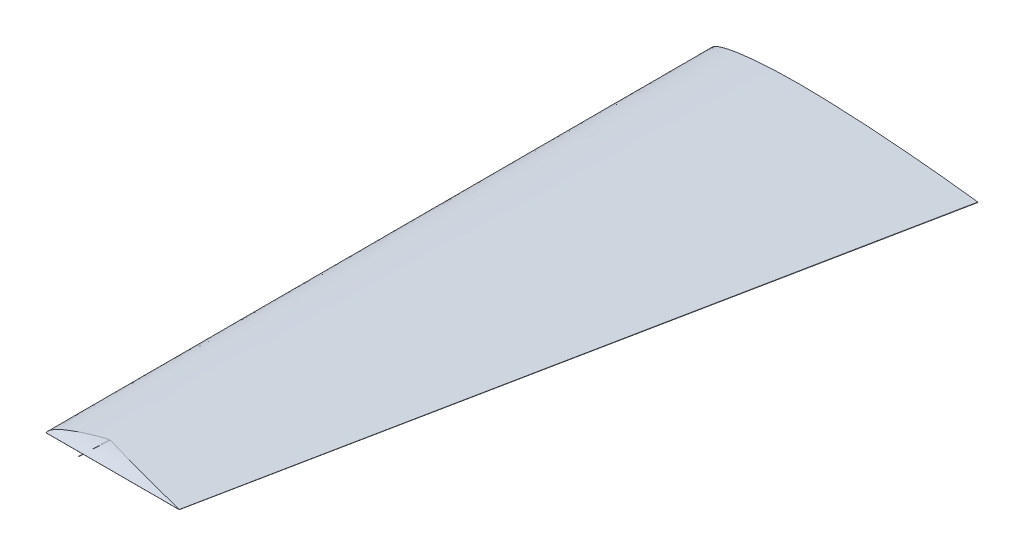
SolidWorks part; units mm, degrees
ref_plane "Front Plane" through (0, 0, 0) normal (0, 0, 1) x (1, 0, 0)
ref_plane "Top Plane" through (0, 0, 0) normal (0, 1, 0) x (1, 0, 0)
ref_plane "Right Plane" through (0, 0, 0) normal (1, 0, 0) x (0, 0, -1)
curve "Curve1"
  spline degree 3 poles (200, 0.17, 0) (196.6775, 0.5867, 0) (190.0326, 1.42, 0) (176.7282, 2.9261, 0) (160.0842, 4.6599, 0) (140.0892, 6.4408, 0) (120.0741, 7.9142, 0) (100.046, 9.0618, 0) (79.9874, 9.8383, 0) (63.2481, 9.9959, 0) (49.8489, 9.6797, 0) (39.8033, 9.2044, 0) (29.7661, 8.4006, 0) (21.4188, 7.4226, 0) (14.7487, 6.3109, 0) (9.7762, 5.2733, 0) (5.5313, 3.9978, 0) (2.2028, 2.7626, 0) (-1.329, -0.0643, 0) (2.4561, -2.5223, 0) (5.8713, -3.4557, 0) (10.1965, -4.3374, 0) (15.2062, -4.9476, 0) (21.8886, -5.5204, 0) (30.2063, -5.9612, 0) (40.1858, -6.1798, 0) (50.1467, -6.2189, 0) (63.418, -6.1197, 0) (80.0231, -5.7775, 0) (99.9664, -5.1377, 0) (119.9393, -4.3294, 0) (139.9252, -3.4016, 0) (159.9318, -2.4016, 0) (176.6142, -1.5068, 0) (189.9743, -0.7666, 0) (196.6568, -0.369, 0) (200, -0.17, 0) knots 0 0 0 0 0.024881 0.04976 0.099487 0.149219 0.198914 0.248605 0.298274 0.348059 0.372958 0.397855 0.422778 0.447754 0.460312 0.472933 0.48573 0.492374 0.501196 0.509997 0.516623 0.529388 0.541926 0.554358 0.579138 0.603839 0.628509 0.653154 0.702452 0.751913 0.801415 0.850979 0.900577 0.950258 0.975115 1 1 1 1
sketch "Sketch1" plane through (0, 0, 0) normal (0, 0, 1) x (1, 0, 0)
  ellipse E0 centre (199.9998, 0.0002) end of major axis (199.8053, 0.0004) minor radius 0.1698 (200.0101, -0.1694) -> (200, 0.17) ccw
  spline S0 degree 3 poles (885.8216, 1859.4461) (495.7124, -79.428) (342.28, -15.8147) (176.7282, 2.9261) (160.0842, 4.6599) (140.0892, 6.4408) (120.0741, 7.9142) (100.046, 9.0618) (79.9874, 9.8383) (63.2481, 9.9959) (49.8489, 9.6797) (39.8033, 9.2044) (29.7661, 8.4006) (21.4188, 7.4226) (14.7487, 6.3109) (9.7762, 5.2733) (5.5313, 3.9978) (2.2028, 2.7626) (-1.329, -0.0643) (2.4561, -2.5223) (5.8713, -3.4557) (10.1965, -4.3374) (15.2062, -4.9476) (21.8886, -5.5204) (30.2063, -5.9612) (40.1858, -6.1798) (50.1467, -6.2189) (63.418, -6.1197) (80.0231, -5.7775) (99.9664, -5.1377) (119.9393, -4.3294) (139.9252, -3.4016) (159.9318, -2.4016) (176.6142, -1.5068) (406.1652, 11.2103) (627.288, 53.9902) (955.0059, -1812.8273) knots -1.138472 -1.138472 -1.138472 -1.138472 0.024881 0.04976 0.099487 0.149219 0.198914 0.248605 0.298274 0.348059 0.372958 0.397855 0.422778 0.447754 0.460312 0.472933 0.48573 0.492374 0.501196 0.509997 0.516623 0.529388 0.541926 0.554358 0.579138 0.603839 0.628509 0.653154 0.702452 0.751913 0.801415 0.850979 0.900577 0.950258 0.975115 2.608853 2.608853 2.608853 2.608853 only from (200, 0.17) to (200, -0.17) construction
  spline S1 degree 3 poles (200, 0.17) (196.6775, 0.5867) (190.0326, 1.42) (176.7282, 2.9261) (160.0842, 4.6599) (140.0892, 6.4408) (120.0741, 7.9142) (100.046, 9.0618) (79.9874, 9.8383) (63.2481, 9.9959) (49.8489, 9.6797) (39.8033, 9.2044) (29.7661, 8.4006) (21.4188, 7.4226) (14.7487, 6.3109) (9.7762, 5.2733) (5.5313, 3.9978) (2.2028, 2.7626) (-1.329, -0.0643) (2.4561, -2.5223) (5.8713, -3.4557) (10.1965, -4.3374) (15.2062, -4.9476) (21.8886, -5.5204) (30.2063, -5.9612) (40.1858, -6.1798) (50.1467, -6.2189) (63.418, -6.1197) (80.0231, -5.7775) (99.9664, -5.1377) (119.9393, -4.3294) (139.9252, -3.4016) (159.9318, -2.4016) (176.6142, -1.5068) (189.9776, -0.7664) (196.6635, -0.3686) (200.0101, -0.1694) knots 0 0 0 0 0.024881 0.04976 0.099487 0.149219 0.198914 0.248605 0.298274 0.348059 0.372958 0.397855 0.422778 0.447754 0.460312 0.472933 0.48573 0.492374 0.501196 0.509997 0.516623 0.529388 0.541926 0.554358 0.579138 0.603839 0.628509 0.653154 0.702452 0.751913 0.801415 0.850979 0.900577 0.950258 0.975115 1.000025 1.000025 1.000025 1.000025
ref_plane "Plane1" through (0, 0, 500) normal (0, 0, 1) x (1, 0, 0)
curve "Curve5"
  spline degree 3 poles (100, 0.08, 0) (98.3405, 0.2906, 0) (95.0201, 0.7118, 0) (88.3671, 1.4611, 0) (80.0448, 2.341, 0) (70.042, 3.2097, 0) (60.0357, 3.9596, 0) (50.0213, 4.5302, 0) (39.9937, 4.9197, 0) (31.6258, 4.9969, 0) (24.9243, 4.8416, 0) (19.902, 4.5944, 0) (14.8795, 4.2015, 0) (10.7092, 3.7129, 0) (7.3761, 3.1547, 0) (4.8922, 2.6348, 0) (2.7648, 2.0026, 0) (1.1046, 1.3748, 0) (-0.665, -0.0316, 0) (1.2285, -1.2612, 0) (2.9335, -1.7282, 0) (5.096, -2.1607, 0) (7.6008, -2.4764, 0) (10.9444, -2.7587, 0) (15.1066, -2.9752, 0) (20.0929, -3.0828, 0) (25.0733, -3.1129, 0) (31.7073, -3.0495, 0) (40.0115, -2.8896, 0) (49.9852, -2.5782, 0) (59.971, -2.156, 0) (69.9643, -1.6971, 0) (79.9641, -1.194, 0) (88.3039, -0.7534, 0) (94.984, -0.3843, 0) (98.3268, -0.1815, 0) (100, -0.08, 0) knots 0 0 0 0 0.02486 0.049739 0.099494 0.149222 0.198943 0.24861 0.298279 0.348065 0.372939 0.397887 0.422784 0.447785 0.460294 0.472915 0.485736 0.49239 0.501194 0.509994 0.51662 0.529357 0.541897 0.554379 0.579134 0.60386 0.62848 0.65315 0.702448 0.751909 0.801438 0.850977 0.900576 0.950232 0.975088 1 1 1 1
sketch "Sketch8" plane through (0, 0, 500) normal (0, 0, 1) x (1, 0, 0)
  ellipse E0 centre (100, 0) end of major axis (100.0982, 0) minor radius 0.08 (100, -0.08) -> (100, 0.08) ccw
  spline S0 degree 3 poles (610.1015, 1926.9997) (277.2849, -58.4947) (186.7781, -9.6222) (88.3671, 1.4611) (80.0448, 2.341) (70.042, 3.2097) (60.0357, 3.9596) (50.0213, 4.5302) (39.9937, 4.9197) (31.6258, 4.9969) (24.9243, 4.8416) (19.902, 4.5944) (14.8795, 4.2015) (10.7092, 3.7129) (7.3761, 3.1547) (4.8922, 2.6348) (2.7648, 2.0026) (1.1046, 1.3748) (-0.665, -0.0316) (1.2285, -1.2612) (2.9335, -1.7282) (5.096, -2.1607) (7.6008, -2.4764) (10.9444, -2.7587) (15.1066, -2.9752) (20.0929, -3.0828) (25.0733, -3.1129) (31.7073, -3.0495) (40.0115, -2.8896) (49.9852, -2.5782) (59.971, -2.156) (69.9643, -1.6971) (79.9641, -1.194) (88.3039, -0.7534) (221.5079, 6.6074) (349.795, 40.9391) (592.8579, -1925.435) knots -1.372215 -1.372215 -1.372215 -1.372215 0.02486 0.049739 0.099494 0.149222 0.198943 0.24861 0.298279 0.348065 0.372939 0.397887 0.422784 0.447785 0.460294 0.472915 0.485736 0.49239 0.501194 0.509994 0.51662 0.529357 0.541897 0.554379 0.579134 0.60386 0.62848 0.65315 0.702448 0.751909 0.801438 0.850977 0.900576 0.950232 0.975088 2.883134 2.883134 2.883134 2.883134 only from (100, 0.08) to (100, -0.08) construction
  spline S1 degree 3 poles (100, 0.08) (98.3405, 0.2906) (95.0201, 0.7118) (88.3671, 1.4611) (80.0448, 2.341) (70.042, 3.2097) (60.0357, 3.9596) (50.0213, 4.5302) (39.9937, 4.9197) (31.6258, 4.9969) (24.9243, 4.8416) (19.902, 4.5944) (14.8795, 4.2015) (10.7092, 3.7129) (7.3761, 3.1547) (4.8922, 2.6348) (2.7648, 2.0026) (1.1046, 1.3748) (-0.665, -0.0316) (1.2285, -1.2612) (2.9335, -1.7282) (5.096, -2.1607) (7.6008, -2.4764) (10.9444, -2.7587) (15.1066, -2.9752) (20.0929, -3.0828) (25.0733, -3.1129) (31.7073, -3.0495) (40.0115, -2.8896) (49.9852, -2.5782) (59.971, -2.156) (69.9643, -1.6971) (79.9641, -1.194) (88.3039, -0.7534) (94.984, -0.3843) (98.3268, -0.1815) (100, -0.08) knots 0 0 0 0 0.02486 0.049739 0.099494 0.149222 0.198943 0.24861 0.298279 0.348065 0.372939 0.397887 0.422784 0.447785 0.460294 0.472915 0.485736 0.49239 0.501194 0.509994 0.51662 0.529357 0.541897 0.554379 0.579134 0.60386 0.62848 0.65315 0.702448 0.751909 0.801438 0.850977 0.900576 0.950232 0.975088 1 1 1 1
loft "Loft3" add profiles "Sketch8", "Sketch1"
sketch "Sketch24" plane through (0, 0, 0) normal (0, 1, 0) x (1, 0, 0)
  line L0 (-0.0006, -489.7783) -> (102.0443, -489.7783)
  line L1 (-0.0006, -489.7783) -> (-0.0006, -508.9308)
  line L2 (-0.0006, -508.9308) -> (105.9387, -508.9308)
  line L3 (200, 0) -> (100, -500) construction
  line L4 (102.0443, -489.7783) -> (102.0443, -508.9308)
  spline S0 degree 2 poles (-0.0006, -489.7783) (50.9437, -502.485) (102.0443, -489.7783) knots 0 0 0 1 1 1
sketch "Sketch30" plane through (0, 0, 0) normal (1, 0, 0) x (0, 0, -1)
  line L0 (-500, 0.0504) -> (-500, 0)
  line L1 (-500, 0.0504) -> (-500, 0)
  line L2 (-500, -3.1005) -> (-500, 4.9584)
  line L3 (-500, -3.1005) -> (-500, 4.9584)
  line L4 (-500, 4.9584) -> (0, 9.9161)
  line L5 (-500, 4.9584) -> (0, 9.9161)
  line L6 (0, 9.9161) -> (0, -6.1951)
  line L7 (0, 9.9161) -> (0, -6.1951)
  line L8 (0, -6.1951) -> (-500, -3.1005)
  line L9 (0, -6.1951) -> (-500, -3.1005)
  line L10 (-484.6006, 5.1111) -> (-500, 4.9584)
  spline S0 degree 2 poles (-500, 0.0504) (-493.4778, 5.2153) (-484.6006, 5.1111) knots 0 0 0 1 1 1
  spline S1 degree 2 poles (-500, 0) (-496.6285, -3.0333) (-491.9796, -3.1501) knots 0 0 0 1 1 1
extrude "Cut-Extrude3" cut sketch "Sketch30" along normal blind 124 contours L3 S0 L5 | S1 L3 L9
